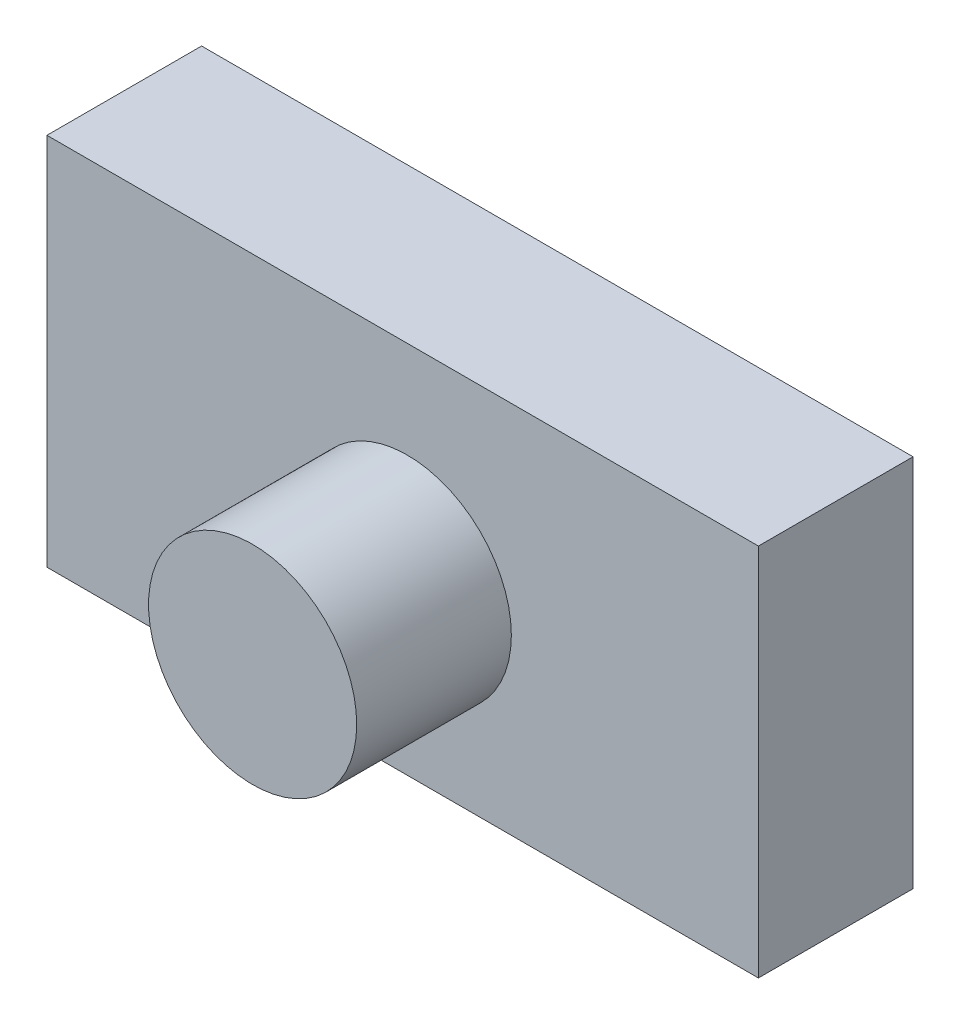
SolidWorks part; units mm, degrees
ref_plane "Front Plane" through (0, 0, 0) normal (0, 0, 1) x (1, 0, 0)
ref_plane "Top Plane" through (0, 0, 0) normal (0, 1, 0) x (1, 0, 0)
ref_plane "Right Plane" through (0, 0, 0) normal (1, 0, 0) x (0, 0, -1)
sketch "Sketch1" plane through (0, 0, 0) normal (0, 0, 1) x (1, 0, 0)
  line L1 (-48.9301, 27.2699) -> (47.6834, 27.2699)
  line L2 (-48.9301, 27.2699) -> (-48.9301, -23.5301)
  line L3 (-48.9301, -23.5301) -> (47.6834, -23.5301)
  line L4 (47.6834, 27.2699) -> (47.6834, -23.5301)
  dimension "D1" = 50.8
extrude "Boss-Extrude1" add sketch "Sketch1" along normal blind 21 contours L1 L4 L3 L2
ref_plane "Plane1" through (-48.9301, 27.2699, 21) normal (1, 0, 0) x (0, 0, -1)
sketch "Sketch4" plane through (0, 0, 21) normal (0, 0, 1) x (1, 0, 0)
  circle A0 centre (0, 0) radius 14.1342
extrude "Boss-Extrude2" add sketch "Sketch4" along normal blind 21
